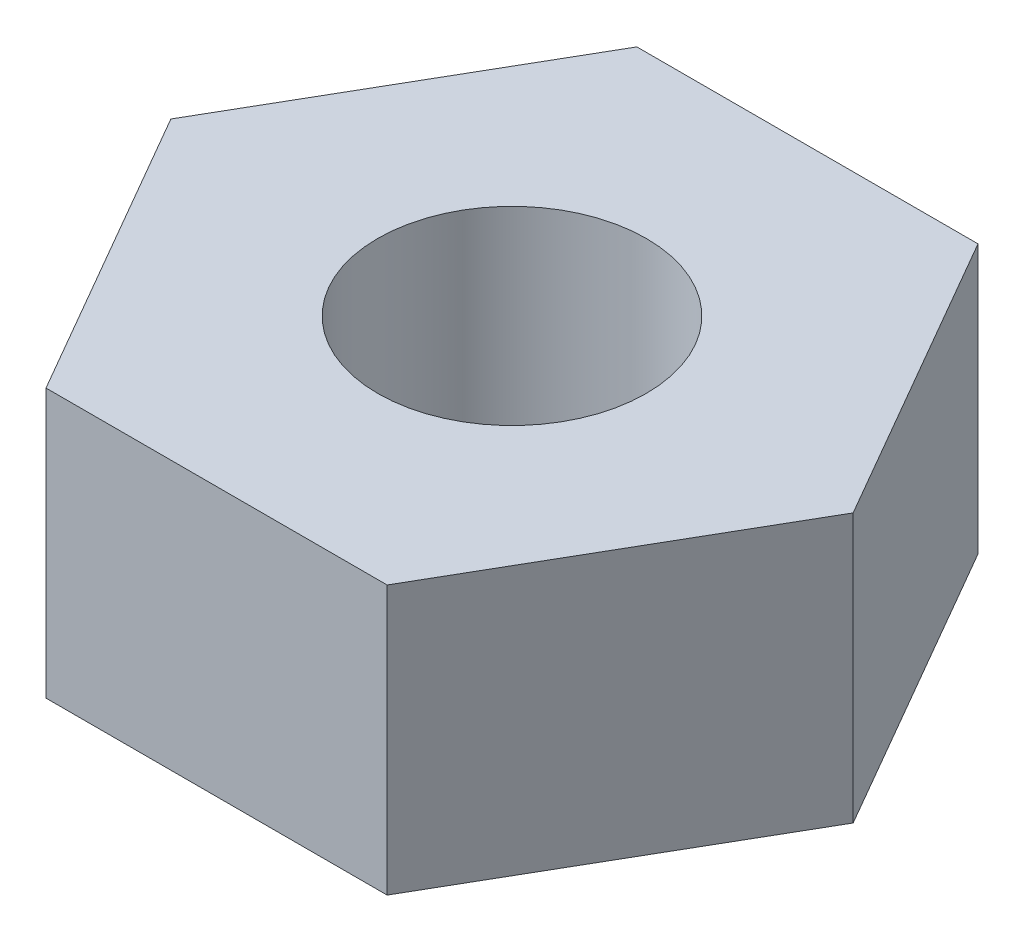
SolidWorks part; units mm, degrees
material "PVC Rigid"
ref_plane "Front Plane" through (0, 0, 0) normal (0, 0, 1) x (1, 0, 0)
ref_plane "Top Plane" through (0, 0, 0) normal (0, 1, 0) x (1, 0, 0)
ref_plane "Right Plane" through (0, 0, 0) normal (1, 0, 0) x (0, 0, -1)
sketch "Sketch1" plane through (0, 0, 0) normal (0, 1, 0) x (1, 0, 0)
  line L1 (3.1754, 0) -> (1.5877, 2.75)
  line L2 (1.5877, 2.75) -> (-1.5877, 2.75)
  line L3 (-1.5877, 2.75) -> (-3.1754, 0)
  line L4 (-3.1754, 0) -> (-1.5877, -2.75)
  line L5 (-1.5877, -2.75) -> (1.5877, -2.75)
  line L6 (1.5877, -2.75) -> (3.1754, 0)
  circle A0 centre (0, 0) radius 2.75 construction
  dimension "D1" = 5.5
extrude "Boss-Extrude1" add sketch "Sketch1" along normal mid plane 2.5
hole_wizard "M3 Tapped Hole1" positions "Sketch2" profile "Sketch3" tap size "M3" standard "ISO" end condition through all
sketch "Sketch2" plane through (0, 1.25, 0) normal (0, 1, 0) x (1, 0, 0)
  point P0 (0, 0)
sketch "Sketch3" plane through (0, 1.25, 0) normal (1, 0, 0) x (0, 0, 1)
  line L0 (0, 0) -> (0, 2.5)
  line L1 (0, 2.5) -> (1.25, 2.5)
  line L2 (1.25, 2.5) -> (1.25, 0)
  line L5 (1.25, 0) -> (0, 0)
  line L11 (0, -6.35) -> (0, 107.95) construction
  dimension "Thru Tap Drill Dia." = 2.5
  dimension "Thru Tap Drill Depth" = 2.5
cosmetic thread "Hole Thread1"
